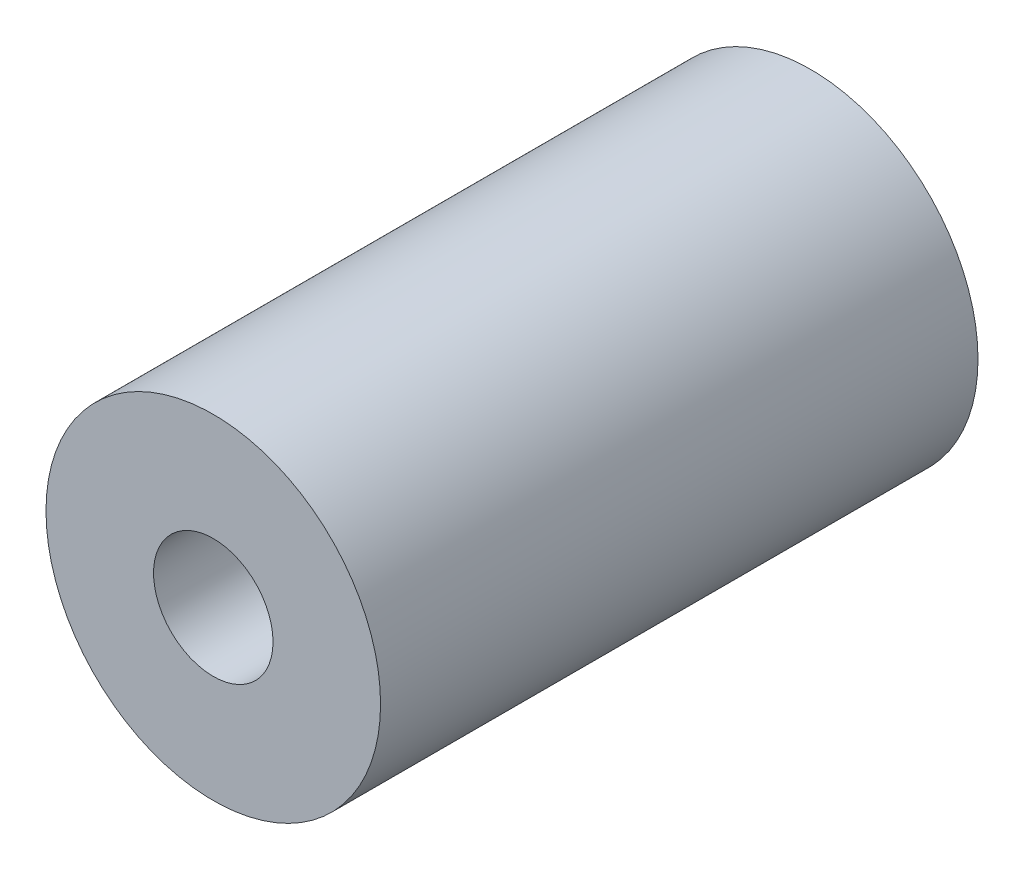
SolidWorks part; units mm, degrees
ref_plane "前视基准面" through (0, 0, 0) normal (0, 0, 1) x (1, 0, 0)
ref_plane "上视基准面" through (0, 0, 0) normal (0, 1, 0) x (1, 0, 0)
ref_plane "右视基准面" through (0, 0, 0) normal (1, 0, 0) x (0, 0, -1)
sketch "草图1" plane through (0, 0, 0) normal (0, 0, 1) x (1, 0, 0)
  circle A0 centre (0, 0) radius 7
extrude "凸台-拉伸1" add sketch "草图1" along normal blind 25
sketch "草图2" plane through (0, 0, 25) normal (0, 0, 1) x (1, 0, 0)
  circle A0 centre (0, 0) radius 2.5
extrude "切除-拉伸1" cut sketch "草图2" against normal blind 12.5
sketch "草图3" plane through (0, 0, 0) normal (0, 0, -1) x (-1, 0, 0)
  circle A0 centre (0, 0) radius 4
extrude "切除-拉伸2" cut sketch "草图3" against normal blind 15
